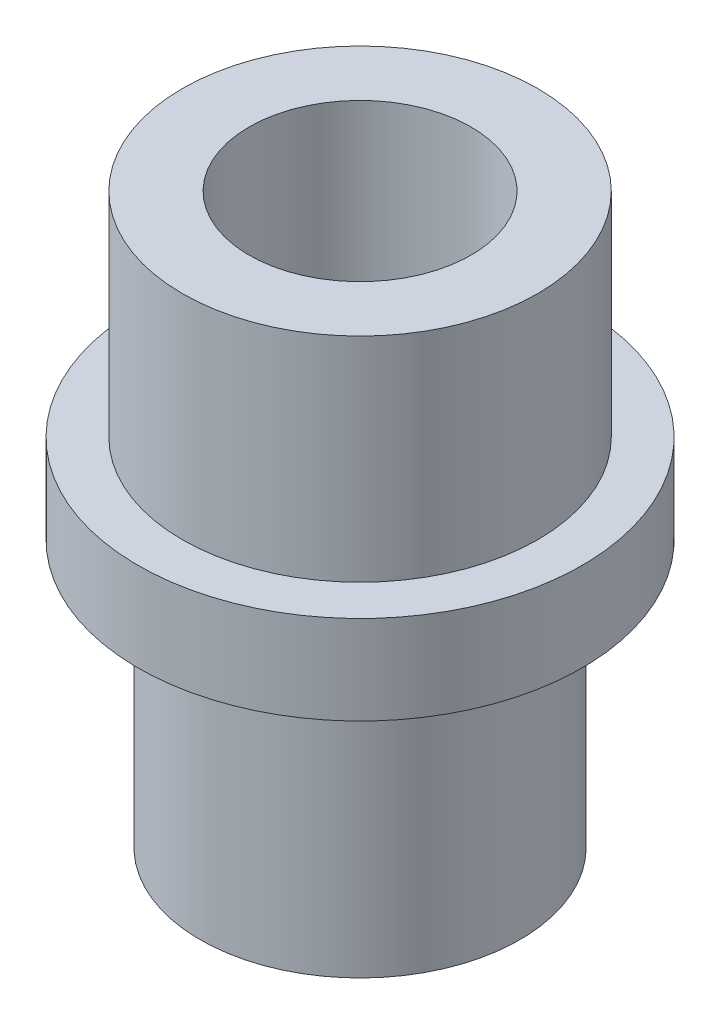
SolidWorks part; units mm, degrees
ref_plane "前视基准面" through (0, 0, 0) normal (0, 0, 1) x (1, 0, 0)
ref_plane "上视基准面" through (0, 0, 0) normal (0, 1, 0) x (1, 0, 0)
ref_plane "右视基准面" through (0, 0, 0) normal (1, 0, 0) x (0, 0, -1)
other "Configuration Table"
sketch "草图1" plane through (0, 0, 0) normal (0, 0, 1) x (1, 0, 0)
  line L0 (0, 13.91) -> (0, 0.5) construction
  line L1 (1, 0) -> (1.8, 0)
  line L2 (1.8, 0) -> (1.8, 3)
  line L3 (1.8, 3) -> (2.5, 3)
  line L4 (2.5, 3) -> (2.5, 4)
  line L5 (2.5, 4) -> (2, 4)
  line L6 (2, 4) -> (2, 6.4)
  line L7 (2, 6.4) -> (1.25, 6.4)
  line L8 (1.25, 6.4) -> (1.25, 2.4)
  line L9 (1.25, 2.4) -> (0, 2.4)
  line L10 (0, 0.5) -> (0, 2.4)
  line L11 (0, 0.5) -> (1, 0.5)
  line L12 (1, 0.5) -> (1, 0)
  line L13 (0, 0) -> (0, -14.8768) construction
  dimension "D2" = 3
  dimension "D3" = 2
  dimension "D4" = 0.5
  dimension "D5" = 1
  dimension "D6" = 1.25
  dimension "D7" = 2.4
  dimension "D8" = 4
  dimension "D9" = 1
  dimension "D10" = 0.5
  dimension "D11" = 1.8
revolve "旋转1" add sketch "草图1" angle 360 about L0
